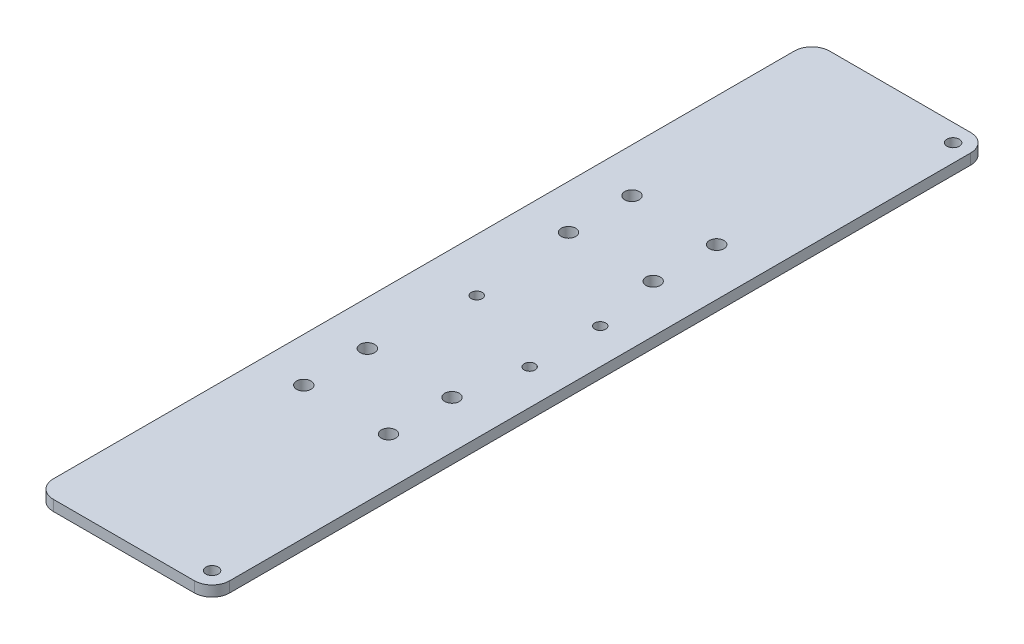
SolidWorks part; units mm, degrees
ref_plane "Front Plane" through (0, 0, 0) normal (0, 0, 1) x (1, 0, 0)
ref_plane "Top Plane" through (0, 0, 0) normal (0, 1, 0) x (1, 0, 0)
ref_plane "Right Plane" through (0, 0, 0) normal (1, 0, 0) x (0, 0, -1)
sketch "Sketch1" plane through (0, 0, 0) normal (0, 1, 0) x (1, 0, 0)
  line L1 (-25, 110) -> (25, 110)
  line L2 (-25, 110) -> (-25, -110)
  line L3 (-25, -110) -> (25, -110)
  line L4 (25, 110) -> (25, -110)
  dimension "D1" = 50
  dimension "D2" = 220
  dimension "D3" = 25
  dimension "D4" = 110
extrude "Extrude1" add sketch "Sketch1" along normal blind 3
sketch "Sketch2" plane through (0, 3, 0) normal (0, 1, 0) x (1, 0, 0)
  line L0 (25, 110) -> (20, 110) construction
  line L1 (25, 110) -> (-25, 110) construction
  line L2 (20, 110) -> (20, 105) construction
  circle A0 centre (20, 105) radius 1.75
  dimension "D3" = 3.5
  dimension "D1" = 5
  dimension "D2" = 5
extrude "Extrude2" cut sketch "Sketch2" against normal blind 3
sketch "Sketch3" plane through (0, 3, 0) normal (0, 1, 0) x (1, 0, 0)
  line L0 (0, 0) -> (0, 37.5) construction
  line L1 (-12.5, 46.5) -> (11.5, 28.5) construction
  line L2 (-12.5, 46.5) -> (11.5, 46.5)
  line L3 (-12.5, 46.5) -> (-12.5, 28.5)
  line L4 (-12.5, 28.5) -> (11.5, 28.5)
  line L5 (11.5, 46.5) -> (11.5, 28.5)
  circle A0 centre (-12.5, 46.5) radius 2.05
  circle A1 centre (11.5, 46.5) radius 2.05
  circle A2 centre (-12.5, 28.5) radius 2.05
  circle A3 centre (11.5, 28.5) radius 2.05
  dimension "D6" = 4.1
  dimension "D7" = 4.1
  dimension "D8" = 4.1
  dimension "D9" = 4.1
  dimension "D1" = 37.5
  dimension "D2" = 24
  dimension "D3" = 18
  dimension "D4" = 12.5
  dimension "D5" = 9
extrude "Extrude3" cut sketch "Sketch3" against normal blind 3 contours A0 | A1 | A2 | A3
sketch "Sketch4" plane through (0, 3, 0) normal (0, 1, 0) x (1, 0, 0)
  line L0 (-10, 0) -> (15, 0) construction
  line L1 (15, 10) -> (15, -10) construction
  circle A0 centre (15, 10) radius 1.55
  circle A1 centre (15, -10) radius 1.55
  circle A2 centre (-10, 0) radius 1.55
  dimension "D5" = 3.1
  dimension "D6" = 3.1
  dimension "D7" = 3.1
  dimension "D1" = 25
  dimension "D2" = 10
  dimension "D3" = 10
  dimension "D4" = 20
extrude "Extrude4" cut sketch "Sketch4" against normal blind 3
pattern_linear "LPattern1" count 2 spacing 210 along (0, 0, 1) of "Extrude2"
pattern_linear "LPattern2" count 2 spacing 75 along (0, 0, 1) of "Extrude3"
fillet "Fillet1" radius 5 4 edges at (25, 1.5, -110) (-25, 1.5, -110) (-25, 1.5, 110) (25, 1.5, 110)
